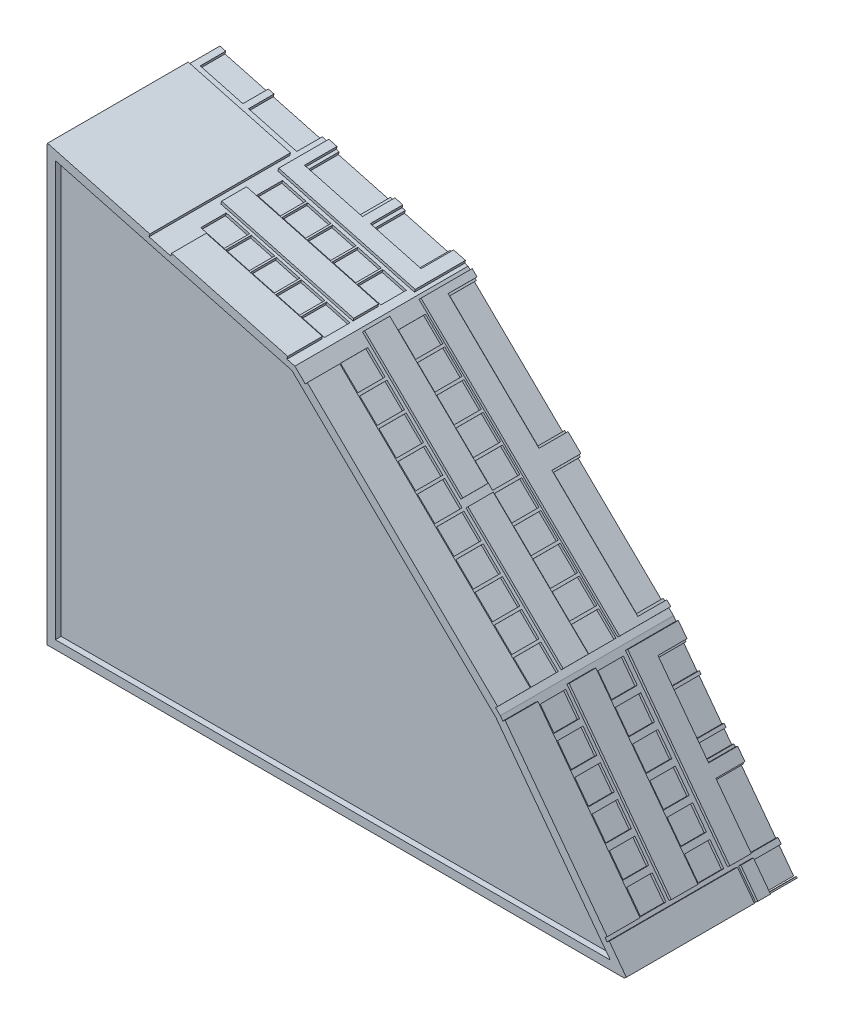
SolidWorks part; units mm, degrees
ref_plane "Front Plane" through (0, 0, 0) normal (0, 0, 1) x (1, 0, 0)
ref_plane "Top Plane" through (0, 0, 0) normal (0, 1, 0) x (1, 0, 0)
ref_plane "Right Plane" through (0, 0, 0) normal (1, 0, 0) x (0, 0, -1)
sketch "Sketch1" plane through (0, 0, 0) normal (0, 0, 1) x (1, 0, 0)
  line L0 (0, 0) -> (0, 149.6295)
  line L1 (0, 0) -> (200, 0)
  line L2 (0, 0) -> (0, 200)
  line L3 (0, 200) -> (200, 200)
  line L4 (200, 0) -> (200, 200)
  line L5 (0, 149.6295) -> (85.9495, 126.5494)
  line L6 (85.9495, 126.5494) -> (157.1252, 57.2758)
  line L7 (157.1252, 57.2758) -> (200, 0)
  dimension "D1" = 200
  dimension "D2" = 200
extrude "Boss-Extrude1" add sketch "Sketch1" against normal blind 60 contours L7 L6 L5 L0 L1
sketch "Sketch2" plane through (128.1762, 95.9484, 0) normal (0.8006, 0.5993, 0) x (0, 0, -1)
  line L0 (60, -119.8531) -> (0, -119.8531) construction
  line L1 (0, -119.8531) -> (44.3726, -119.8531)
  line L2 (0, -119.8531) -> (0, -109.9951)
  line L3 (0, -109.9951) -> (44.3726, -109.9951)
  line L4 (44.3726, -119.8531) -> (44.3726, -109.9951)
  line L5 (45.5667, -119.8531) -> (49.9364, -119.8531)
  line L6 (45.5667, -119.8531) -> (45.5667, -109.9951)
  line L7 (45.5667, -109.9951) -> (49.9364, -109.9951)
  line L8 (49.9364, -119.8531) -> (49.9364, -109.9951)
  line L9 (0, -48.3075) -> (0, -119.8531) construction
  line L10 (0, -108.7768) -> (11.3639, -108.7768)
  line L11 (0, -108.7768) -> (0, -49.7784)
  line L12 (0, -49.7784) -> (11.3639, -49.7784)
  line L13 (11.3639, -108.7768) -> (11.3639, -49.7784)
  line L14 (60, -48.3075) -> (60, -119.8531) construction
  line L15 (22.1863, -108.7768) -> (31.437, -108.7768)
  line L16 (22.1863, -108.7768) -> (22.1863, -49.7784)
  line L17 (22.1863, -49.7784) -> (31.437, -49.7784)
  line L18 (31.437, -108.7768) -> (31.437, -49.7784)
  line L19 (42.487, -108.7768) -> (49.9364, -108.7768)
  line L20 (42.487, -108.7768) -> (42.487, -49.7784)
  line L21 (42.487, -49.7784) -> (49.9364, -49.7784)
  line L22 (49.9364, -108.7768) -> (49.9364, -49.7784)
  line L23 (49.9364, -88.2937) -> (60, -88.2937)
  line L24 (49.9364, -88.2937) -> (49.9364, -84.0803)
  line L25 (49.9364, -84.0803) -> (60, -84.0803)
  line L26 (60, -88.2937) -> (60, -84.0803)
  line L28 (49.9364, -54.7704) -> (60, -54.7704)
  line L29 (49.9364, -54.7704) -> (49.9364, -49.7784)
  line L30 (49.9364, -49.7784) -> (60, -49.7784)
  line L31 (60, -54.7704) -> (60, -49.7784)
  line M1 (0, -48.3075) -> (0, -119.8531)
  line M2 (0, -119.8531) -> (60, -119.8531)
  line M3 (60, -119.8531) -> (60, -48.3075)
extrude "Boss-Extrude2" add sketch "Sketch2" along normal blind 1 contours L10 L13 L12 M1 | L4 L3 M2 M1 | L15 L18 L17 L16 | L19 L22 L21 L20 | L8 L7 L6 M2 | L25 L22 L23 M3 | L30 L22 L28 M3
sketch "Sketch3" plane through (128.1762, 95.9484, 0) normal (0.8006, 0.5993, 0) x (0, 0, -1)
  line L0 (11.3639, -108.7768) -> (11.3639, -49.7784) construction
  line L1 (12.3639, -108.7675) -> (21.1863, -108.7675)
  line L2 (12.3639, -108.7675) -> (12.3639, -100.7675)
  line L3 (12.3639, -100.7675) -> (21.1863, -100.7675)
  line L4 (21.1863, -108.7675) -> (21.1863, -100.7675)
  line L5 (22.1863, -108.7768) -> (22.1863, -49.7784) construction
  line L6 (32.3639, -108.7675) -> (41.1863, -108.7675)
  line L7 (32.3639, -108.7675) -> (32.3639, -100.7675)
  line L8 (32.3639, -100.7675) -> (41.1863, -100.7675)
  line L9 (41.1863, -108.7675) -> (41.1863, -100.7675)
  line L10 (32.3639, -98.7675) -> (41.1863, -98.7675)
  line L11 (32.3639, -98.7675) -> (32.3639, -90.7675)
  line L12 (32.3639, -90.7675) -> (41.1863, -90.7675)
  line L13 (41.1863, -98.7675) -> (41.1863, -90.7675)
  line L14 (32.3639, -88.7675) -> (41.1863, -88.7675)
  line L15 (32.3639, -88.7675) -> (32.3639, -80.7675)
  line L16 (32.3639, -80.7675) -> (41.1863, -80.7675)
  line L17 (41.1863, -88.7675) -> (41.1863, -80.7675)
  line L18 (32.3639, -78.7675) -> (41.1863, -78.7675)
  line L19 (32.3639, -78.7675) -> (32.3639, -70.7675)
  line L20 (32.3639, -70.7675) -> (41.1863, -70.7675)
  line L21 (41.1863, -78.7675) -> (41.1863, -70.7675)
  line L22 (32.3639, -68.7675) -> (41.1863, -68.7675)
  line L23 (32.3639, -68.7675) -> (32.3639, -60.7675)
  line L24 (32.3639, -60.7675) -> (41.1863, -60.7675)
  line L25 (41.1863, -68.7675) -> (41.1863, -60.7675)
  line L26 (32.3639, -58.7675) -> (41.1863, -58.7675)
  line L27 (32.3639, -58.7675) -> (32.3639, -50.7675)
  line L28 (32.3639, -50.7675) -> (41.1863, -50.7675)
  line L29 (41.1863, -58.7675) -> (41.1863, -50.7675)
  line L30 (12.3639, -98.7675) -> (21.1863, -98.7675)
  line L31 (12.3639, -98.7675) -> (12.3639, -90.7675)
  line L32 (12.3639, -90.7675) -> (21.1863, -90.7675)
  line L33 (21.1863, -98.7675) -> (21.1863, -90.7675)
  line L34 (12.3639, -88.7675) -> (21.1863, -88.7675)
  line L35 (12.3639, -88.7675) -> (12.3639, -80.7675)
  line L36 (12.3639, -80.7675) -> (21.1863, -80.7675)
  line L37 (21.1863, -88.7675) -> (21.1863, -80.7675)
  line L38 (12.3639, -78.7675) -> (21.1863, -78.7675)
  line L39 (12.3639, -78.7675) -> (12.3639, -70.7675)
  line L40 (12.3639, -70.7675) -> (21.1863, -70.7675)
  line L41 (21.1863, -78.7675) -> (21.1863, -70.7675)
  line L42 (12.3639, -68.7675) -> (21.1863, -68.7675)
  line L43 (12.3639, -68.7675) -> (12.3639, -60.7675)
  line L44 (12.3639, -60.7675) -> (21.1863, -60.7675)
  line L45 (21.1863, -68.7675) -> (21.1863, -60.7675)
  line L46 (12.3639, -58.7675) -> (21.1863, -58.7675)
  line L47 (12.3639, -58.7675) -> (12.3639, -50.7675)
  line L48 (12.3639, -50.7675) -> (21.1863, -50.7675)
  line L49 (21.1863, -58.7675) -> (21.1863, -50.7675)
  line L50 (60, -88.2937) -> (60, -119.8531) construction
  line L51 (50.6441, -119.4186) -> (60, -119.4186)
  line L52 (50.6441, -119.4186) -> (50.6441, -110.5894)
  line L53 (50.6441, -110.5894) -> (60, -110.5894)
  line L54 (60, -119.4186) -> (60, -110.5894)
  line L55 (60, -54.7704) -> (60, -84.0803) construction
  line L56 (50.6441, -108.7675) -> (60, -108.7675)
  line L57 (50.6441, -108.7675) -> (50.6441, -88.7675)
  line L58 (50.6441, -88.7675) -> (60, -88.7675)
  line L59 (60, -108.7675) -> (60, -88.7675)
  line L60 (50.6441, -83.268) -> (60, -83.268)
  line L61 (50.6441, -83.268) -> (50.6441, -78.7675)
  line L62 (50.6441, -78.7675) -> (60, -78.7675)
  line L63 (60, -83.268) -> (60, -78.7675)
  line L65 (50.6441, -77.6202) -> (60, -77.6202)
  line L66 (50.6441, -77.6202) -> (50.6441, -64.2725)
  line L67 (50.6441, -64.2725) -> (60, -64.2725)
  line L68 (60, -77.6202) -> (60, -64.2725)
  line L69 (50.6441, -63.2858) -> (60, -63.2858)
  line L70 (50.6441, -63.2858) -> (50.6441, -55.4447)
  line L71 (50.6441, -55.4447) -> (60, -55.4447)
  line L72 (60, -63.2858) -> (60, -55.4447)
  dimension "D1" = 1
  dimension "D2" = 1
  dimension "D3" = 8
  dimension "D4" = 2
  dimension "D5" = 6
extrude "Cut-Extrude1" cut sketch "Sketch3" against normal blind 1
sketch "Sketch4" plane through (105.0624, 107.9473, 0) normal (0.6975, 0.7166, 0) x (0.7166, -0.6975, 0)
  line L0 (-26.671, 0) -> (72.6508, 0) construction
  line L1 (70.3963, 0) -> (-21.6365, 0)
  line L2 (70.3963, 0) -> (70.3963, 11.2579)
  line L3 (70.3963, 11.2579) -> (-21.6365, 11.2579)
  line L4 (-21.6365, 0) -> (-21.6365, 11.2579)
  line L5 (-26.671, 60) -> (72.6508, 60) construction
  line L6 (70.3963, 22.7058) -> (24.3799, 22.7058)
  line L7 (70.3963, 22.7058) -> (70.3963, 31.4427)
  line L8 (70.3963, 31.4427) -> (24.3799, 31.4427)
  line L9 (24.3799, 22.7058) -> (24.3799, 31.4427)
  line L10 (21.8738, 22.7058) -> (-25.6358, 22.7058)
  line L11 (21.8738, 22.7058) -> (21.8738, 31.4427)
  line L12 (21.8738, 31.4427) -> (-25.6358, 31.4427)
  line L13 (-25.6358, 22.7058) -> (-25.6358, 31.4427)
  line L14 (70.3963, 42.2719) -> (-25.6358, 42.2719)
  line L15 (70.3963, 42.2719) -> (70.3963, 49.9606)
  line L16 (70.3963, 49.9606) -> (-25.6358, 49.9606)
  line L17 (-25.6358, 42.2719) -> (-25.6358, 49.9606)
  line L18 (26.9377, 49.9606) -> (20.6843, 49.9606)
  line L19 (26.9377, 49.9606) -> (26.9377, 60)
  line L20 (26.9377, 60) -> (20.6843, 60)
  line L21 (20.6843, 49.9606) -> (20.6843, 60)
  line L23 (70.3963, 49.9606) -> (68.4641, 49.9606)
  line L24 (70.3963, 49.9606) -> (70.3963, 60)
  line L25 (70.3963, 60) -> (68.4641, 60)
  line L26 (68.4641, 49.9606) -> (68.4641, 60)
  line L27 (-25.6358, 49.9606) -> (-23.2682, 49.9606)
  line L28 (-25.6358, 49.9606) -> (-25.6358, 60)
  line L29 (-25.6358, 60) -> (-23.2682, 60)
  line L30 (-23.2682, 49.9606) -> (-23.2682, 60)
  line M1 (-26.671, 0) -> (72.6508, 0)
  line M3 (72.6508, 60) -> (-26.671, 60)
extrude "Boss-Extrude3" add sketch "Sketch4" along normal blind 1 contours L4 L2 L3 M1 | L9 L6 L7 L8 | L13 L10 L11 L12 | L17 L14 L15 L16 | L21 L16 L19 M3 | L24 L25 L26 L23 | L27 L30 L29 L28
sketch "Sketch5" plane through (105.0624, 107.9473, 0) normal (0.6975, 0.7166, 0) x (0.7166, -0.6975, 0)
  line L0 (70.3963, 11.2579) -> (-21.6365, 11.2579) construction
  line L1 (70.3963, 12.2579) -> (61.9963, 12.2579)
  line L2 (70.3963, 12.2579) -> (70.3963, 21.7058)
  line L3 (70.3963, 21.7058) -> (61.9963, 21.7058)
  line L4 (61.9963, 12.2579) -> (61.9963, 21.7058)
  line L5 (70.3963, 22.7058) -> (24.3799, 22.7058) construction
  line L6 (70.3963, 0) -> (70.3963, 11.2579) construction
  line L7 (52.6963, 12.2579) -> (52.6963, 21.7058)
  line L8 (61.0963, 21.7058) -> (52.6963, 21.7058)
  line L9 (61.0963, 12.2579) -> (61.0963, 21.7058)
  line L10 (61.0963, 12.2579) -> (52.6963, 12.2579)
  line L11 (43.3963, 12.2579) -> (43.3963, 21.7058)
  line L12 (51.7963, 21.7058) -> (43.3963, 21.7058)
  line L13 (51.7963, 12.2579) -> (51.7963, 21.7058)
  line L14 (51.7963, 12.2579) -> (43.3963, 12.2579)
  line L15 (34.0963, 12.2579) -> (34.0963, 21.7058)
  line L16 (42.4963, 21.7058) -> (34.0963, 21.7058)
  line L17 (42.4963, 12.2579) -> (42.4963, 21.7058)
  line L18 (42.4963, 12.2579) -> (34.0963, 12.2579)
  line L19 (24.7963, 12.2579) -> (24.7963, 21.7058)
  line L20 (33.1963, 21.7058) -> (24.7963, 21.7058)
  line L21 (33.1963, 12.2579) -> (33.1963, 21.7058)
  line L22 (33.1963, 12.2579) -> (24.7963, 12.2579)
  line L23 (15.4963, 12.2579) -> (15.4963, 21.7058)
  line L24 (23.8963, 21.7058) -> (15.4963, 21.7058)
  line L25 (23.8963, 12.2579) -> (23.8963, 21.7058)
  line L26 (23.8963, 12.2579) -> (15.4963, 12.2579)
  line L27 (6.1963, 12.2579) -> (6.1963, 21.7058)
  line L28 (14.5963, 21.7058) -> (6.1963, 21.7058)
  line L29 (14.5963, 12.2579) -> (14.5963, 21.7058)
  line L30 (14.5963, 12.2579) -> (6.1963, 12.2579)
  line L31 (-3.1037, 12.2579) -> (-3.1037, 21.7058)
  line L32 (5.2963, 21.7058) -> (-3.1037, 21.7058)
  line L33 (5.2963, 12.2579) -> (5.2963, 21.7058)
  line L34 (5.2963, 12.2579) -> (-3.1037, 12.2579)
  line L35 (-12.4037, 12.2579) -> (-12.4037, 21.7058)
  line L36 (-4.0037, 21.7058) -> (-12.4037, 21.7058)
  line L37 (-4.0037, 12.2579) -> (-4.0037, 21.7058)
  line L38 (-4.0037, 12.2579) -> (-12.4037, 12.2579)
  line L39 (-21.7037, 12.2579) -> (-21.7037, 21.7058)
  line L40 (-13.3037, 21.7058) -> (-21.7037, 21.7058)
  line L41 (-13.3037, 12.2579) -> (-13.3037, 21.7058)
  line L42 (-13.3037, 12.2579) -> (-21.7037, 12.2579)
  line L43 (52.6963, 32.2579) -> (52.6963, 41.7058)
  line L44 (61.0963, 41.7058) -> (52.6963, 41.7058)
  line L45 (61.0963, 32.2579) -> (61.0963, 41.7058)
  line L46 (61.0963, 32.2579) -> (52.6963, 32.2579)
  line L47 (43.3963, 32.2579) -> (43.3963, 41.7058)
  line L48 (51.7963, 41.7058) -> (43.3963, 41.7058)
  line L49 (51.7963, 32.2579) -> (51.7963, 41.7058)
  line L50 (51.7963, 32.2579) -> (43.3963, 32.2579)
  line L51 (34.0963, 32.2579) -> (34.0963, 41.7058)
  line L52 (42.4963, 41.7058) -> (34.0963, 41.7058)
  line L53 (42.4963, 32.2579) -> (42.4963, 41.7058)
  line L54 (42.4963, 32.2579) -> (34.0963, 32.2579)
  line L55 (24.7963, 32.2579) -> (24.7963, 41.7058)
  line L56 (33.1963, 41.7058) -> (24.7963, 41.7058)
  line L57 (33.1963, 32.2579) -> (33.1963, 41.7058)
  line L58 (33.1963, 32.2579) -> (24.7963, 32.2579)
  line L59 (15.4963, 32.2579) -> (15.4963, 41.7058)
  line L60 (23.8963, 41.7058) -> (15.4963, 41.7058)
  line L61 (23.8963, 32.2579) -> (23.8963, 41.7058)
  line L62 (23.8963, 32.2579) -> (15.4963, 32.2579)
  line L63 (6.1963, 32.2579) -> (6.1963, 41.7058)
  line L64 (14.5963, 41.7058) -> (6.1963, 41.7058)
  line L65 (14.5963, 32.2579) -> (14.5963, 41.7058)
  line L66 (14.5963, 32.2579) -> (6.1963, 32.2579)
  line L67 (-3.1037, 32.2579) -> (-3.1037, 41.7058)
  line L68 (5.2963, 41.7058) -> (-3.1037, 41.7058)
  line L69 (5.2963, 32.2579) -> (5.2963, 41.7058)
  line L70 (5.2963, 32.2579) -> (-3.1037, 32.2579)
  line L71 (-12.4037, 32.2579) -> (-12.4037, 41.7058)
  line L72 (-4.0037, 41.7058) -> (-12.4037, 41.7058)
  line L73 (-4.0037, 32.2579) -> (-4.0037, 41.7058)
  line L74 (-4.0037, 32.2579) -> (-12.4037, 32.2579)
  line L75 (-21.7037, 32.2579) -> (-21.7037, 41.7058)
  line L76 (-13.3037, 41.7058) -> (-21.7037, 41.7058)
  line L77 (-13.3037, 32.2579) -> (-13.3037, 41.7058)
  line L78 (-13.3037, 32.2579) -> (-21.7037, 32.2579)
  line L79 (61.9963, 32.2579) -> (61.9963, 41.7058)
  line L80 (70.3963, 41.7058) -> (61.9963, 41.7058)
  line L81 (70.3963, 32.2579) -> (70.3963, 41.7058)
  line L82 (70.3963, 32.2579) -> (61.9963, 32.2579)
  line L83 (26.9377, 60) -> (68.4641, 60) construction
  line L84 (67.6922, 50.7424) -> (27.5578, 50.7424)
  line L85 (67.6922, 50.7424) -> (67.6922, 60)
  line L86 (67.6922, 60) -> (27.5578, 60)
  line L87 (27.5578, 50.7424) -> (27.5578, 60)
  line L88 (-23.2682, 60) -> (20.6843, 60) construction
  line L89 (20.0319, 50.7424) -> (-22.6157, 50.7424)
  line L90 (20.0319, 50.7424) -> (20.0319, 60)
  line L91 (20.0319, 60) -> (-22.6157, 60)
  line L92 (-22.6157, 50.7424) -> (-22.6157, 60)
  dimension "D1" = 1
  dimension "D2" = 1
  dimension "D3" = 8.4
  dimension "D4" = 10
  dimension "D5" = 2
extrude "Cut-Extrude2" cut sketch "Sketch5" against normal blind 1
sketch "Sketch6" plane through (37.4777, 139.5656, 0) normal (0.2593, 0.9658, 0) x (0.9658, -0.2593, 0)
  line L0 (-38.8054, 0) -> (50.1891, 0) construction
  line L1 (47.3658, 0) -> (5.6918, 0)
  line L2 (47.3658, 0) -> (47.3658, 12.0123)
  line L3 (47.3658, 12.0123) -> (5.6918, 12.0123)
  line L4 (5.6918, 0) -> (5.6918, 12.0123)
  line L5 (-38.8054, 60) -> (50.1891, 60) construction
  line L6 (47.3658, 22.8407) -> (0, 22.8407)
  line L7 (47.3658, 22.8407) -> (47.3658, 31.4844)
  line L8 (47.3658, 31.4844) -> (0, 31.4844)
  line L9 (0, 22.8407) -> (0, 31.4844)
  line L10 (48.9902, 42.5974) -> (0, 42.5974)
  line L11 (48.9902, 42.5974) -> (48.9902, 60)
  line L12 (48.9902, 60) -> (0, 60)
  line L13 (0, 42.5974) -> (0, 60)
  line L14 (-38.8054, 60) -> (-38.8054, 0) construction
  line L15 (44.725, 48.7346) -> (26.5288, 48.7346)
  line L16 (44.725, 48.7346) -> (44.725, 60)
  line L17 (44.725, 60) -> (26.5288, 60)
  line L18 (26.5288, 48.7346) -> (26.5288, 60)
  line L19 (23.6829, 48.7346) -> (2.9229, 48.7346)
  line L20 (23.6829, 48.7346) -> (23.6829, 60)
  line L21 (23.6829, 60) -> (2.9229, 60)
  line L22 (2.9229, 48.7346) -> (2.9229, 60)
  line L23 (-2.1004, 0) -> (-38.8054, 0)
  line L24 (-2.1004, 0) -> (-2.1004, 48.7346)
  line L25 (-2.1004, 48.7346) -> (-38.8054, 48.7346)
  line L26 (-38.8054, 0) -> (-38.8054, 48.7346)
  line M1 (-38.8054, 0) -> (50.1891, 0)
  line M3 (50.1891, 60) -> (-38.8054, 60)
  line M4 (-38.8054, 60) -> (-38.8054, 0)
extrude "Boss-Extrude4" add sketch "Sketch6" along normal blind 1 contours L4 L2 L3 M1 | L9 L6 L7 L8 | L24 L25 M4 M1 | L19 L22 L13 L10 L11 L16 L15 L18 L20 M3
sketch "Sketch7" plane through (37.4777, 139.5656, 0) normal (0.2593, 0.9658, 0) x (0.9658, -0.2593, 0)
  line L0 (47.3658, 12.0123) -> (5.6918, 12.0123) construction
  line L1 (47.3658, 13.0123) -> (38.9658, 13.0123)
  line L2 (47.3658, 13.0123) -> (47.3658, 21.8407)
  line L3 (47.3658, 21.8407) -> (38.9658, 21.8407)
  line L4 (38.9658, 13.0123) -> (38.9658, 21.8407)
  line L5 (47.3658, 22.8407) -> (0, 22.8407) construction
  line L6 (47.3658, 0) -> (47.3658, 12.0123) construction
  line L7 (38.3658, 13.0123) -> (29.9658, 13.0123)
  line L8 (38.3658, 13.0123) -> (38.3658, 21.8407)
  line L9 (38.3658, 21.8407) -> (29.9658, 21.8407)
  line L10 (29.9658, 13.0123) -> (29.9658, 21.8407)
  line L11 (29.3658, 13.0123) -> (20.9658, 13.0123)
  line L12 (29.3658, 13.0123) -> (29.3658, 21.8407)
  line L13 (29.3658, 21.8407) -> (20.9658, 21.8407)
  line L14 (20.9658, 13.0123) -> (20.9658, 21.8407)
  line L15 (20.3658, 13.0123) -> (11.9658, 13.0123)
  line L16 (20.3658, 13.0123) -> (20.3658, 21.8407)
  line L17 (20.3658, 21.8407) -> (11.9658, 21.8407)
  line L18 (11.9658, 13.0123) -> (11.9658, 21.8407)
  line L19 (11.3658, 13.0123) -> (2.9658, 13.0123)
  line L20 (11.3658, 13.0123) -> (11.3658, 21.8407)
  line L21 (11.3658, 21.8407) -> (2.9658, 21.8407)
  line L22 (2.9658, 13.0123) -> (2.9658, 21.8407)
  line L23 (38.3658, 32.5123) -> (29.9658, 32.5123)
  line L24 (38.3658, 32.5123) -> (38.3658, 41.3407)
  line L25 (38.3658, 41.3407) -> (29.9658, 41.3407)
  line L26 (29.9658, 32.5123) -> (29.9658, 41.3407)
  line L27 (29.3658, 32.5123) -> (20.9658, 32.5123)
  line L28 (29.3658, 32.5123) -> (29.3658, 41.3407)
  line L29 (29.3658, 41.3407) -> (20.9658, 41.3407)
  line L30 (20.9658, 32.5123) -> (20.9658, 41.3407)
  line L31 (20.3658, 32.5123) -> (11.9658, 32.5123)
  line L32 (20.3658, 32.5123) -> (20.3658, 41.3407)
  line L33 (20.3658, 41.3407) -> (11.9658, 41.3407)
  line L34 (11.9658, 32.5123) -> (11.9658, 41.3407)
  line L35 (11.3658, 32.5123) -> (2.9658, 32.5123)
  line L36 (11.3658, 32.5123) -> (11.3658, 41.3407)
  line L37 (11.3658, 41.3407) -> (2.9658, 41.3407)
  line L38 (2.9658, 32.5123) -> (2.9658, 41.3407)
  line L39 (47.3658, 32.5123) -> (38.9658, 32.5123)
  line L40 (47.3658, 32.5123) -> (47.3658, 41.3407)
  line L41 (47.3658, 41.3407) -> (38.9658, 41.3407)
  line L42 (38.9658, 32.5123) -> (38.9658, 41.3407)
  line L43 (26.5288, 60) -> (44.725, 60) construction
  line L44 (43.786, 49.4885) -> (27.6922, 49.4885)
  line L45 (43.786, 49.4885) -> (43.786, 60)
  line L46 (43.786, 60) -> (27.6922, 60)
  line L47 (27.6922, 49.4885) -> (27.6922, 60)
  line L48 (2.9229, 60) -> (23.6829, 60) construction
  line L49 (22.357, 49.4885) -> (3.9556, 49.4885)
  line L50 (22.357, 49.4885) -> (22.357, 60)
  line L51 (22.357, 60) -> (3.9556, 60)
  line L52 (3.9556, 49.4885) -> (3.9556, 60)
  line L53 (-38.8054, 60) -> (0, 60) construction
  line L54 (-2.1004, 51.1622) -> (-19.4027, 51.1622)
  line L55 (-2.1004, 51.1622) -> (-2.1004, 60)
  line L56 (-2.1004, 60) -> (-19.4027, 60)
  line L57 (-19.4027, 51.1622) -> (-19.4027, 60)
  line L59 (-21.4327, 51.1622) -> (-36.7243, 51.1622)
  line L60 (-21.4327, 51.1622) -> (-21.4327, 60)
  line L61 (-21.4327, 60) -> (-36.7243, 60)
  line L62 (-36.7243, 51.1622) -> (-36.7243, 60)
  dimension "D1" = 1
  dimension "D2" = 1
  dimension "D3" = 8.4
  dimension "D4" = 5
  dimension "D5" = 2
extrude "Cut-Extrude3" cut sketch "Sketch7" against normal blind 1
sketch "Sketch8" plane through (0, 0, 0) normal (0, 0, 1) x (1, 0, 0)
  line L0 (3, 146.7531) -> (3, 3)
  line L1 (3, 3) -> (195.256, 3)
  line L2 (195.256, 3) -> (155.618, 55.9519)
  line L3 (155.618, 55.9519) -> (84.9278, 124.7529)
  line L4 (84.9278, 124.7529) -> (3, 146.7531)
  line L5 (0, 0) -> (0, 149.6295) construction
  line L6 (0, 0) -> (200, 0) construction
  line L7 (158.8072, 56.6976) -> (194.1629, 9.4664) construction
  line L8 (90.2548, 123.7546) -> (156.2071, 59.5648) construction
  line L9 (43.2341, 139.0552) -> (83.4822, 128.2474) construction
  dimension "D1" = 3
  dimension "D2" = 3
  dimension "D3" = 3
  dimension "D4" = 3
  dimension "D5" = 3
extrude "Cut-Extrude4" cut sketch "Sketch8" against normal blind 2
sketch "Sketch9" plane through (0, 0, -60) normal (0, 0, -1) x (-1, 0, 0)
  line L0 (-3, 145.7176) -> (-3, 3)
  line L1 (-3, 3) -> (-194.0069, 3)
  line L2 (-194.0069, 3) -> (-154.8644, 55.2899)
  line L3 (-154.8644, 55.2899) -> (-84.417, 123.8547)
  line L4 (-84.417, 123.8547) -> (-3, 145.7176)
  line L5 (-35.4491, 140.1103) -> (-37.4777, 139.5656) construction
  line L6 (-119.8852, 93.5207) -> (-88.388, 124.1761) construction
  line L7 (-178.5626, 28.6379) -> (-160.9982, 52.102) construction
  line L8 (0, 0) -> (0, 149.6295) construction
  line L9 (0, 0) -> (-198.7509, 0) construction
  line L10 (-181.8881, 25.8642) -> (-179.3632, 29.2372) construction
  line L11 (-125.0639, 89.8757) -> (-120.5826, 94.2373) construction
  line L12 (-40.5599, 139.7733) -> (-37.737, 140.5314) construction
  dimension "D1" = 3
  dimension "D2" = 3
  dimension "D3" = 4
  dimension "D4" = 4
  dimension "D5" = 4
extrude "Cut-Extrude5" cut sketch "Sketch9" against normal offset from surface (55 mm away) 3 up to face at (88.3604, 66.6916, -2)
